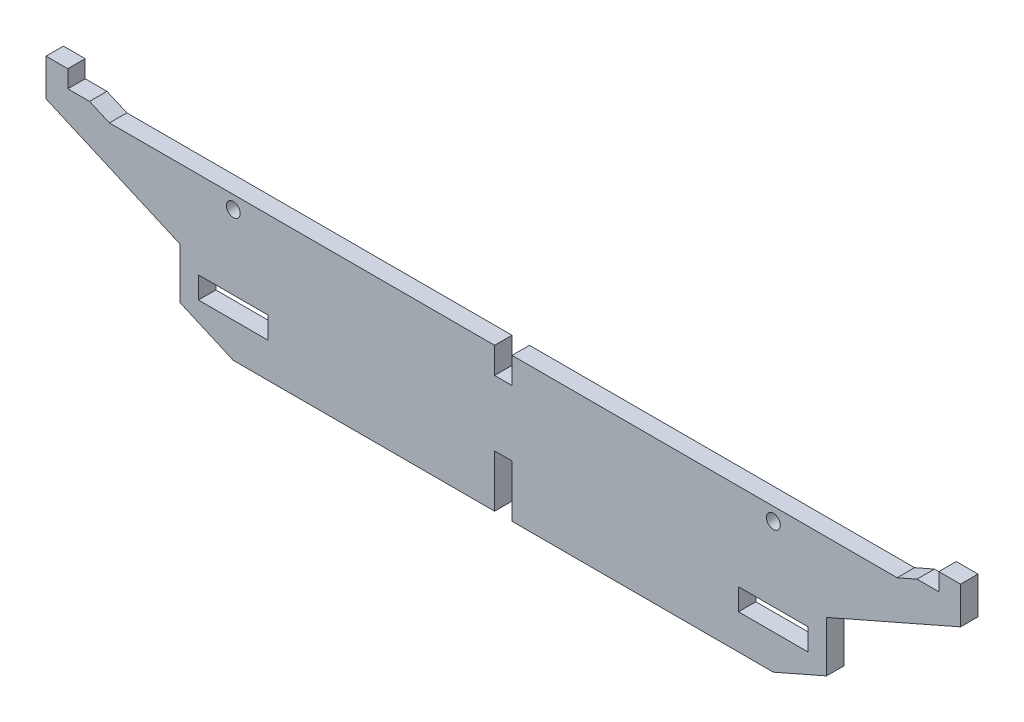
SolidWorks part; units mm, degrees
ref_plane "Front Plane" through (0, 0, 0) normal (0, 0, 1) x (1, 0, 0)
ref_plane "Top Plane" through (0, 0, 0) normal (0, 1, 0) x (1, 0, 0)
ref_plane "Right Plane" through (0, 0, 0) normal (1, 0, 0) x (0, 0, -1)
sketch "Sketch1" plane through (0, 0, 0) normal (0, 0, 1) x (1, 0, 0)
  line L0 (0, -43.0686) -> (0, 56.6488) construction
  line L1 (-95, 17) -> (-100, 17)
  line L2 (54, 8) -> (70, 8) construction
  line L3 (54, 8) -> (54, -8) construction
  line L4 (54, -8) -> (70, -8) construction
  line L5 (70, 8) -> (70, -8) construction
  line L6 (100, 17) -> (100, 21)
  line L7 (100, 21) -> (105, 21)
  line L8 (105, 21) -> (105, 12.5004)
  line L9 (74.2147, -12.6434) -> (62, -18)
  line L10 (62, -18) -> (2, -18)
  line L11 (54, 8) -> (70, -8) construction
  line L12 (70, 8) -> (54, -8) construction
  line L13 (-70, 8) -> (-54, -8) construction
  line L14 (-54, 8) -> (-70, -8) construction
  line L15 (-70, 8) -> (-70, -8) construction
  line L16 (-54, -8) -> (-70, -8) construction
  line L17 (-54, 8) -> (-54, -8) construction
  line L18 (-54, 8) -> (-70, 8) construction
  line L19 (-74.2147, -12.6434) -> (-62, -18)
  line L20 (-105, 21) -> (-105, 12.5004)
  line L21 (-100, 21) -> (-105, 21)
  line L22 (-100, 17) -> (-100, 21)
  line L23 (95, 17) -> (90.4394, 15)
  line L24 (90.4394, 15) -> (2, 15)
  line L25 (95, 17) -> (100, 17)
  line L26 (-95, 17) -> (-90.4394, 15)
  line L27 (2, 15) -> (2, 9)
  line L28 (-62, 0) -> (62, 0) construction
  line L29 (2, 9) -> (-2, 9)
  line L30 (2, -18) -> (2, -6)
  line L31 (2, -6) -> (-2, -6)
  line L32 (-2, 15) -> (-90.4394, 15)
  line L33 (-2, -18) -> (-62, -18)
  line L34 (-2, -18) -> (-2, -6)
  line L35 (-2, 15) -> (-2, 9)
  line L36 (-74.2147, -12.6434) -> (-74.2147, -1)
  line L37 (-74.2147, -1) -> (-105, 12.5004)
  line L38 (74.2147, -12.6434) -> (74.2147, -1)
  line L39 (74.2147, -1) -> (105, 12.5004)
  point P7 (-62, 0)
  point P9 (62, 0)
  point P20 (0, 0)
  point P24 (0, 40)
  point P27 (73.331, 42)
  point P30 (0, 40)
  point P31 (73.331, 17)
  point P32 (99.8, 42)
  point P38 (98.8347, 49.7973)
  point P52 (0, -6)
  point P54 (0, 9)
  dimension "D1" = 16
  dimension "D2" = 70
  dimension "D3" = 100
  dimension "D4" = 5
  dimension "D5" = 2
  dimension "D6" = 33
  dimension "D7" = 5
  dimension "D8" = 15
  dimension "D10" = 4
  dimension "D11" = 15
  dimension "D13" = 4
  dimension "D9" = 12
extrude "Boss-Extrude1" add sketch "Sketch1" along normal blind 4
sketch "Sketch2" plane through (0, 0, 4) normal (0, 0, 1) x (1, 0, 0)
  line L1 (54, -5) -> (70, -5)
  line L2 (54, -5) -> (54, -10)
  line L3 (54, -10) -> (70, -10)
  line L4 (70, -5) -> (70, -10)
  line L7 (54, -7) -> (54, 9) construction
  line L8 (54, -7) -> (70, -7) construction
  line L9 (54, 9) -> (70, 9) construction
  line L10 (70, -7) -> (70, 9) construction
  line L11 (54, -7) -> (70, 9) construction
  line L12 (54, 9) -> (70, -7) construction
  line L13 (100, 17) -> (95, 17) construction
  circle A0 centre (62, 12) radius 1.6
  point P7 (62, 1)
  dimension "D2" = 3.2
  dimension "D3" = 11
  dimension "D1" = 62
  dimension "D4" = 19
  dimension "D5" = 5
  dimension "D6" = 16
  dimension "D7" = 16
extrude "Cut-Extrude1" cut sketch "Sketch2" against normal through all
mirror "Mirror1" about plane through (0, 0, 0) normal (1, 0, 0) of "Cut-Extrude1"
